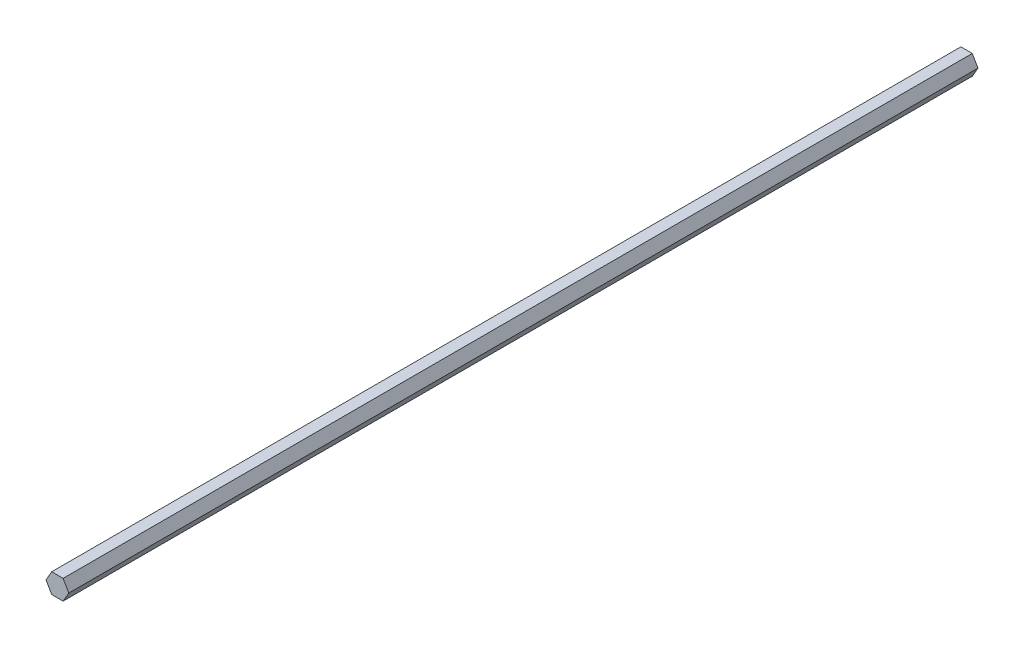
SolidWorks part; units mm, degrees
material "7075-T6 (SN)"
ref_plane "Front Plane" through (0, 0, 0) normal (0, 0, 1) x (1, 0, 0)
ref_plane "Top Plane" through (0, 0, 0) normal (0, 1, 0) x (1, 0, 0)
ref_plane "Right Plane" through (0, 0, 0) normal (1, 0, 0) x (0, 0, -1)
sketch "Sketch1" plane through (0, 0, 0) normal (0, 0, 1) x (1, 0, 0)
  line L1 (7.3323, 0) -> (3.6662, 6.35)
  line L2 (3.6662, 6.35) -> (-3.6662, 6.35)
  line L3 (-3.6662, 6.35) -> (-7.3323, 0)
  line L4 (-7.3323, 0) -> (-3.6662, -6.35)
  line L5 (-3.6662, -6.35) -> (3.6662, -6.35)
  line L6 (3.6662, -6.35) -> (7.3323, 0)
  circle A0 centre (0, 0) radius 6.35 construction
  dimension "D1" = 12.7
extrude "Boss-Extrude1" add sketch "Sketch1" along normal blind 584.2
